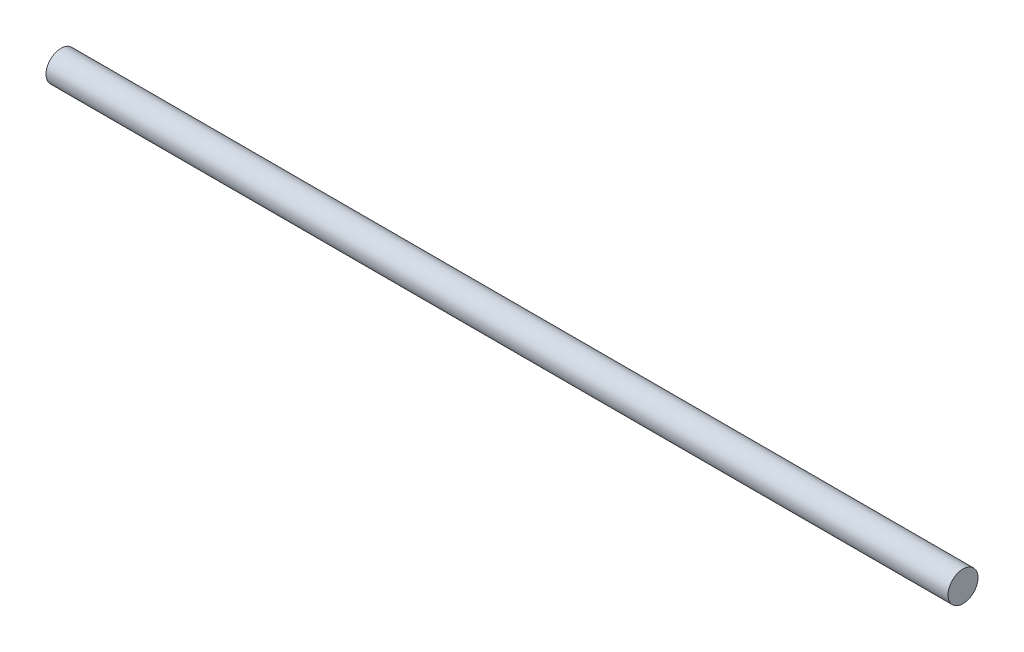
SolidWorks part; units mm, degrees
ref_plane "前视基准面" through (0, 0, 0) normal (0, 0, 1) x (1, 0, 0)
ref_plane "上视基准面" through (0, 0, 0) normal (0, 1, 0) x (1, 0, 0)
ref_plane "右视基准面" through (0, 0, 0) normal (1, 0, 0) x (0, 0, -1)
sketch "草图1" plane through (0, 0, 0) normal (0, 0, 1) x (1, 0, 0)
  line L0 (-126.4588, 0) -> (143.4998, 0) construction
  line L1 (0, 0) -> (0, 0.5)
  line L2 (0, 0.5) -> (30, 0.5)
  line L3 (30, 0.5) -> (30, 0)
  line L4 (0, 0) -> (30, 0)
revolve "旋转1" add sketch "草图1" angle 360 about L0
